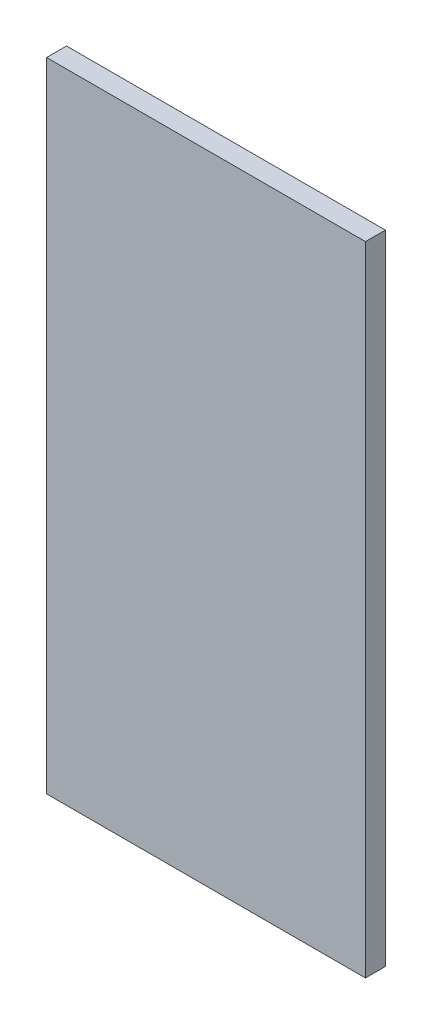
SolidWorks part; units mm, degrees
ref_plane "Front Plane" through (0, 0, 0) normal (0, 0, 1) x (1, 0, 0)
ref_plane "Top Plane" through (0, 0, 0) normal (0, 1, 0) x (1, 0, 0)
ref_plane "Right Plane" through (0, 0, 0) normal (1, 0, 0) x (0, 0, -1)
sketch "Sketch1" plane through (0, 0, 0) normal (0, 0, 1) x (1, 0, 0)
  line L1 (0, 0) -> (50.8, 0)
  line L2 (0, 0) -> (0, 101.6)
  line L3 (0, 101.6) -> (50.8, 101.6)
  line L4 (50.8, 0) -> (50.8, 101.6)
  dimension "D1" = 50.8
  dimension "D2" = 101.6
extrude "Boss-Extrude1" add sketch "Sketch1" along normal blind 3.175
